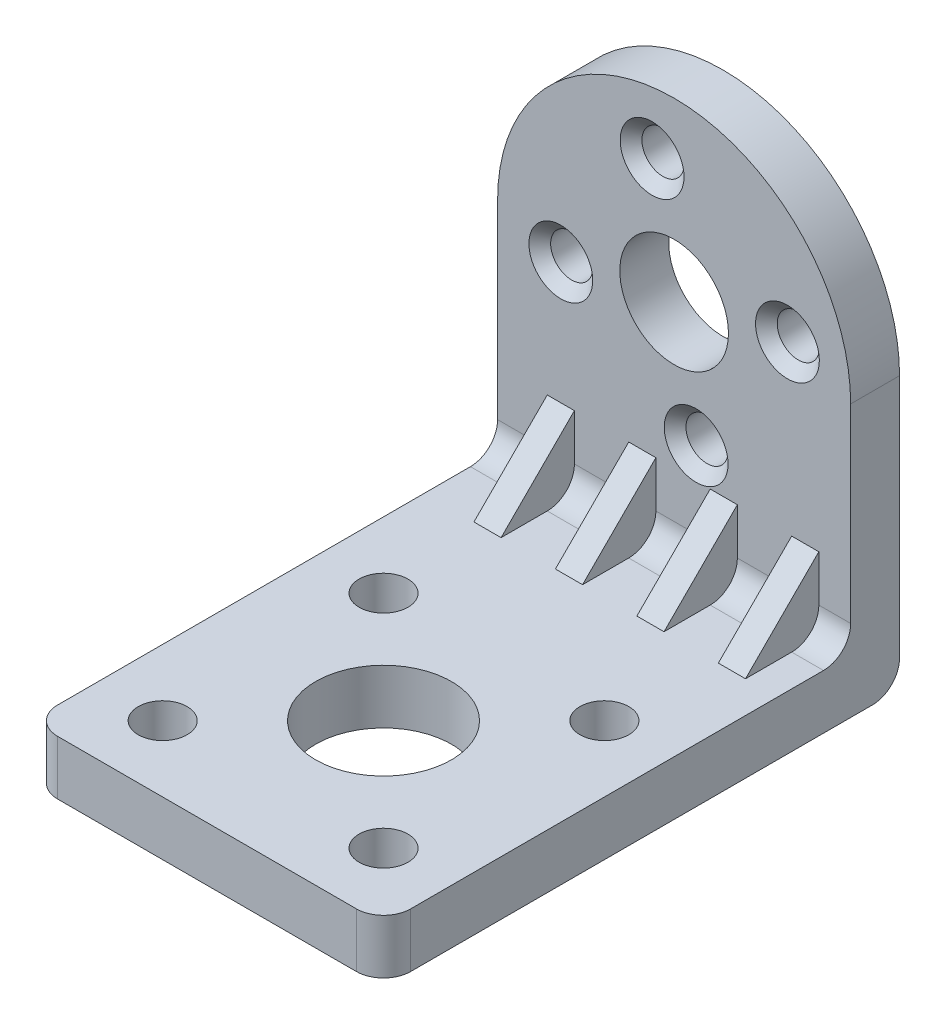
SolidWorks part; units mm, degrees
ref_plane "前视基准面" through (0, 0, 0) normal (0, 0, 1) x (1, 0, 0)
ref_plane "上视基准面" through (0, 0, 0) normal (0, 1, 0) x (1, 0, 0)
ref_plane "右视基准面" through (0, 0, 0) normal (1, 0, 0) x (0, 0, -1)
sketch "草图2" plane through (0, 0, 0) normal (0, 1, 0) x (1, 0, 0)
  line L0 (8.1317, -8.1317) -> (-8.1317, 8.1317) construction
  line L1 (-13, 25) -> (13, 25)
  line L2 (-13, 25) -> (-13, -13)
  line L3 (-13, -13) -> (13, -13)
  line L4 (13, 25) -> (13, -13)
  line L5 (0, 0) -> (0, 14.9644) construction
  line L6 (-8.1317, -8.1317) -> (8.1317, 8.1317) construction
  circle A1 centre (-8.1317, 8.1317) radius 1.8
  circle A8 centre (0, 0) radius 11.5 construction
  circle A10 centre (8.1317, 8.1317) radius 1.8
  circle A11 centre (8.1317, -8.1317) radius 1.8
  circle A12 centre (-8.1317, -8.1317) radius 1.8
  circle A13 centre (0, 0) radius 5
  point P23 (0, 0)
  dimension "D3" = 45
  dimension "D4" = 3.6
  dimension "D5" = 4
  dimension "D8" = 23
  dimension "D6" = 10
  dimension "D1" = 38
  dimension "D2" = 26
  dimension "D7" = 13
  dimension "D9" = 25
extrude "凸台-拉伸1" add sketch "草图2" along normal blind 4
sketch "草图3" plane through (0, 0, 0) normal (0, 0, 1) x (1, 0, 0)
  line L0 (-9.6167, 20) -> (9.6167, 20) construction
  line L2 (-13, 20) -> (-13, 4)
  line L3 (-13, 4) -> (13, 4)
  line L5 (9.6167, 20) -> (0, 20) construction
  line L6 (0, 20) -> (0, 11.3844) construction
  line L7 (13, 20) -> (13, 4)
  line L8 (-13, 0) -> (13, 0) construction
  line L9 (0, 20) -> (0, 32.4299) construction
  line L10 (0, 20) -> (-2.3033, 31.8496) construction
  arc A0 (13, 20) -> (-13, 20) centre (0, 20) ccw
  circle A5 centre (0, 20) radius 4
  circle A6 centre (0, 20) radius 8.5 construction
  circle A7 centre (-1.6219, 28.3438) radius 1.55
  circle A8 centre (8.3438, 21.6219) radius 1.55
  circle A9 centre (1.6219, 11.6562) radius 1.55
  circle A10 centre (-8.3438, 18.3781) radius 1.55
  point P10 (0, 20)
  point P24 (0, 20)
  point P29 (0, 20)
  dimension "D1" = 4
  dimension "D6" = 8
  dimension "D7" = 17
  dimension "D9" = 3.1
  dimension "D3" = 20
  dimension "D8" = 11
extrude "凸台-拉伸2" add sketch "草图3" along normal blind 3.6 from vertex at -25 starting at point (13, 4, -25)
fillet "圆角1" radius 2 4 edges at (0, 4, -21.4) (0, 0, -25) (13, 2, 13) (-13, 2, 13)
ref_plane "基准面1" through (-8.3438, 0, 0) normal (-1, 0, 0) x (0, 0, 1)
sketch "草图4" plane through (-8.3438, 0, 0) normal (-1, 0, 0) x (0, 0, 1)
  line L0 (-25, 13) -> (-12.4, 0.4)
  line L1 (-19.4, 4) -> (11, 4) construction
  line L2 (-21.4, 20) -> (-21.4, 6) construction
  line L3 (-25, 20) -> (-25, 2) construction
  dimension "D1" = 9
  dimension "D2" = 9
  dimension "D3" = 45
rib "筋1" sketch "草图4" sketch "草图4" thickness 2 extrusion direction parallel to sketch draft on no parameters "D1"=2
pattern_linear "阵列(线性)1" count 4 spacing 6 along (1, 0, 0) of "筋1"
chamfer "倒角1" distance 0.8 angle 45 4 edges at (3.1719, 11.6562, -21.4) (9.8938, 21.6219, -21.4) (-6.7938, 18.3781, -21.4) (-0.0719, 28.3438, -21.4)
